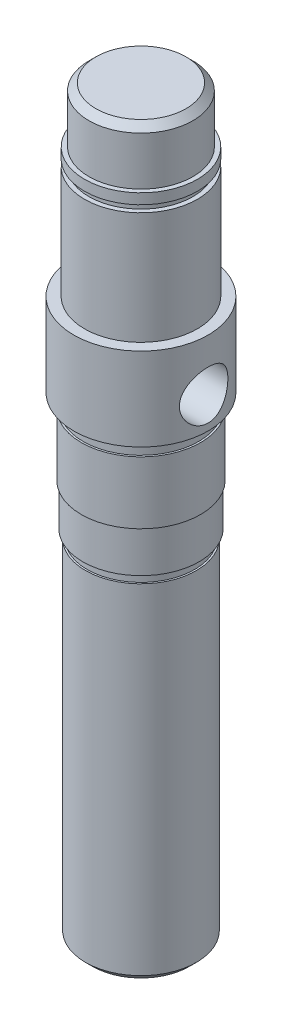
SolidWorks part; units mm, degrees
ref_plane "Plan de face" through (0, 0, 0) normal (0, 0, 1) x (1, 0, 0)
ref_plane "Plan de dessus" through (0, 0, 0) normal (0, 1, 0) x (1, 0, 0)
ref_plane "Plan de droite" through (0, 0, 0) normal (1, 0, 0) x (0, 0, -1)
sketch "Esquisse1" plane through (0, 0, 0) normal (0, 0, 1) x (1, 0, 0)
  line L0 (0, 0) -> (-7, 0)
  line L2 (-7, 0) -> (-8, 1)
  line L4 (-8, 1) -> (-8, 50)
  line L6 (-8, 50) -> (-7.75, 50)
  line L7 (-7.75, 50) -> (-7.75, 51.3)
  line L9 (-7.75, 51.3) -> (-8.4, 51.3)
  line L10 (-8.4, 51.3) -> (-8.4, 57.3)
  line L12 (-8.4, 57.3) -> (-8.6, 57.3)
  line L13 (-8.6, 57.3) -> (-8.6, 66.3)
  line L15 (-8.6, 66.3) -> (-8.33, 66.3)
  line L16 (-8.33, 66.3) -> (-8.33, 68.3)
  line L18 (-8.33, 68.3) -> (-9.7, 68.3)
  line L22 (-9.7, 80.3) -> (-8.15, 80.3)
  line L23 (-8.15, 80.3) -> (-8.15, 96.5)
  line L24 (-8.15, 96.5) -> (-7.5, 96.5)
  line L26 (-7.5, 96.5) -> (-7.5, 97.5)
  line L28 (-7.5, 97.5) -> (-8.15, 97.5)
  line L29 (-8.15, 97.5) -> (-8.15, 99)
  line L31 (-8.15, 99) -> (-7.5, 99)
  line L32 (-7.5, 99) -> (-7.5, 106)
  line L33 (-7.5, 106) -> (-6.5, 107)
  line L35 (-6.5, 107) -> (0, 107)
  line L36 (0, 107) -> (0, 0)
  line L37 (-9.7, 80.3) -> (-9.7, 68.3)
  dimension "D1" = 7
  dimension "D2" = 1
  dimension "D3" = 1
  dimension "D4" = 49
  dimension "D5" = 0.25
  dimension "D6" = 1.3
  dimension "D7" = 0.65
  dimension "D8" = 6
  dimension "D9" = 0.2
  dimension "D10" = 8.6
  dimension "D11" = 0.27
  dimension "D12" = 0.65
  dimension "D13" = 1
  dimension "D14" = 1
  dimension "D15" = 7.5
  dimension "D16" = 0.65
  dimension "D17" = 0.65
  dimension "D18" = 1.37
revolve "Révolution1" add sketch "Esquisse1" angle 360 about L36
sketch "Esquisse2" plane through (0, 0, 0) normal (0, 0, 1) x (1, 0, 0)
  line L0 (-7, 0) -> (7, 0) construction
  line L1 (0, 47.1) -> (0, 0) construction
  line L8 (5.8095, 2.7) -> (5.8095, 47.1)
  line L9 (5.8095, 47.1) -> (-5.8095, 47.1)
  line L10 (-5.8095, 47.1) -> (-5.8095, 2.7)
  line L11 (-5.8095, 2.7) -> (5.8095, 2.7)
  dimension "D1" = 11.619
  dimension "D2" = 44.4
  dimension "D3" = 2.7
extrude "Enlèv. mat.-Extru.1" cut sketch "Esquisse2" against normal through all from offset 5.5 offset against normal yes
sketch "Esquisse5" plane through (0, 0, 0) normal (1, 0, 0) x (0, 0, -1)
  arc A2 (0, 76.3) -> (0, 69.3) centre (0, 72.8) ccw
  arc A3 (0, 69.3) -> (0, 76.3) centre (0, 72.8) ccw
extrude "Enlèv. mat.-Extru.2" cut sketch "Esquisse5" along normal through all
sketch "Esquisse6" plane through (0, 0, 0) normal (0, -1, 0) x (1, 0, 0)
  circle A0 centre (0, 0) radius 3.5
  circle A1 centre (0, 0) radius 7
  circle A2 centre (0, 0) radius 7 construction
  dimension "D2" = 7
  dimension "D1" = 0
extrude "Enlèv. mat.-Extru.3" cut sketch "Esquisse6" against normal blind 78
chamfer "Chanfrein1" distance 1 angle 45 1 edges at (0, 0, -3.5)
